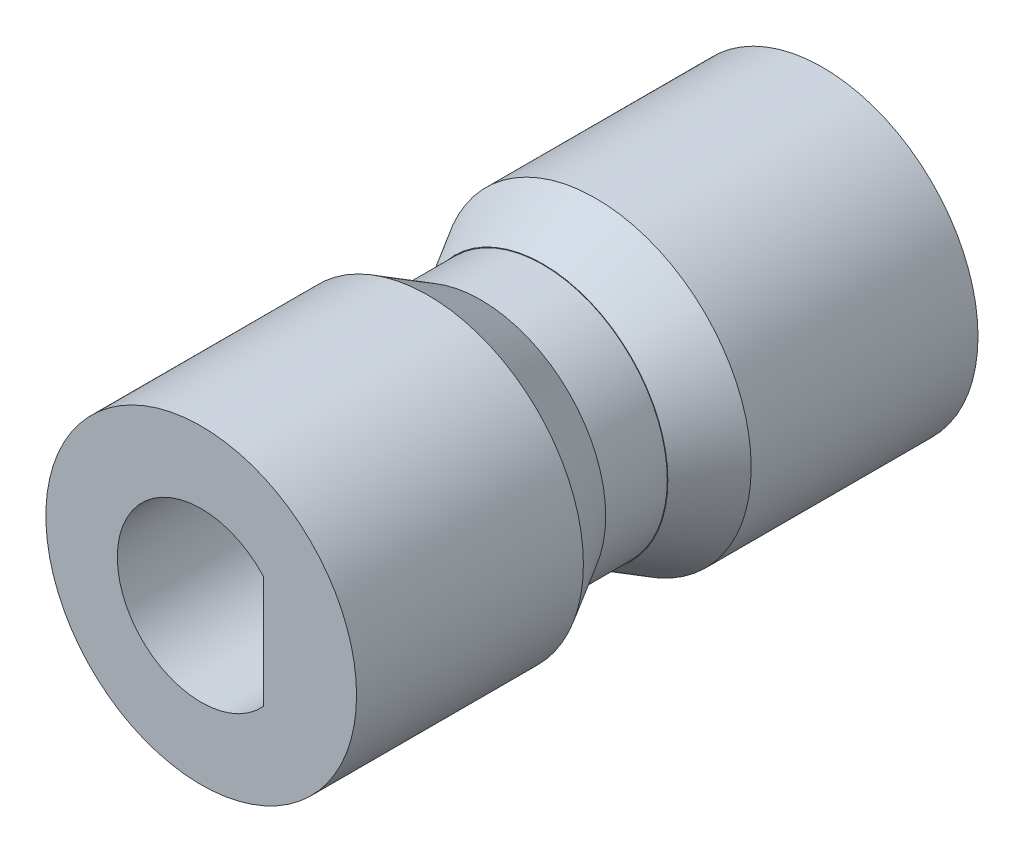
SolidWorks part; units mm, degrees
ref_plane "Спереди" through (0, 0, 0) normal (0, 0, 1) x (1, 0, 0)
ref_plane "Сверху" through (0, 0, 0) normal (0, 1, 0) x (1, 0, 0)
ref_plane "Справа" through (0, 0, 0) normal (1, 0, 0) x (0, 0, -1)
sketch "Эскиз3" plane through (0, 0, 0) normal (0, 0, 1) x (1, 0, 0)
  circle A0 centre (0, 0) radius 5
  dimension "D1" = 10
extrude "Вытянуть2" add sketch "Эскиз3" along normal blind 9
sketch "Эскиз4" plane through (0, 0, 9) normal (0, 0, 1) x (1, 0, 0)
  circle A0 centre (0, 0) radius 4
  dimension "D1" = 8
extrude "Вытянуть3" add sketch "Эскиз4" along normal blind 2
sketch "Эскиз5" plane through (0, 0, 11) normal (0, 0, 1) x (1, 0, 0)
  circle A0 centre (0, 0) radius 5
  circle A1 centre (0, 0) radius 5 construction
extrude "Вытянуть4" add sketch "Эскиз5" along normal blind 9
sketch "Эскиз1" plane through (0, 0, 0) normal (0, 0, 1) x (1, 0, 0)
  line L0 (2, 1.8138) -> (2, -1.8138)
  circle A1 centre (0, 0) radius 2.7 construction
  arc A2 (2, 1.8138) -> (2, -1.8138) centre (0, 0) ccw
  point P6 (-2.7, 0)
  dimension "D2" = 5.4
  dimension "D3" = 4.7
extrude "Вытянуть5" cut sketch "Эскиз1" along normal up to next
chamfer "Фаска2" distance 1.7 angle 30 2 edges at (5, 0, 11) (5, 0, 9)
sketch "Эскиз6" plane through (0, 0, 0) normal (0, 0, -1) x (-1, 0, 0)
